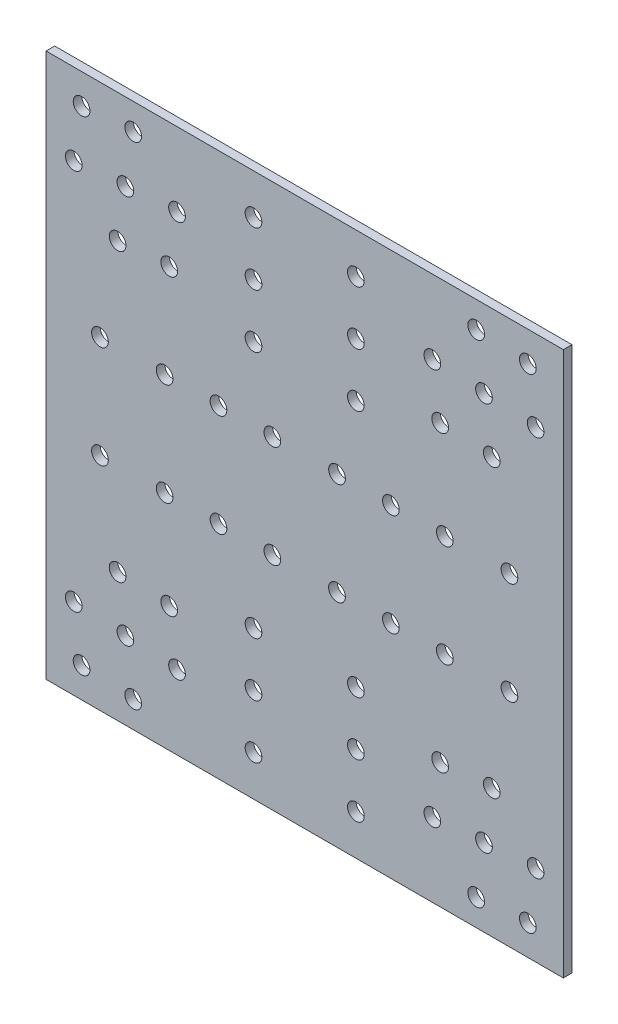
SolidWorks part; units mm, degrees
ref_plane "前视基准面" through (0, 0, 0) normal (0, 0, 1) x (1, 0, 0)
ref_plane "上视基准面" through (0, 0, 0) normal (0, 1, 0) x (1, 0, 0)
ref_plane "右视基准面" through (0, 0, 0) normal (1, 0, 0) x (0, 0, -1)
sketch "草图1" plane through (0, 0, 0) normal (0, 0, 1) x (1, 0, 0)
  line L0 (441.9641, -2319.3154) -> (441.9641, 47680.6846) construction
  line L1 (-38.0359, 30.4879) -> (921.9641, 30.4879)
  line L2 (-38.0359, 30.4879) -> (-38.0359, -979.5121)
  line L3 (-38.0359, -979.5121) -> (921.9641, -979.5121)
  line L4 (921.9641, 30.4879) -> (921.9641, -979.5121)
  line L5 (-192.1047, -474.5121) -> (1362.782, -474.5121) construction
  line L6 (27.879, -923.7944) -> (33913.7262, 35842.3499) construction
  line L7 (109.2051, -835.5556) -> (-167.3802, -580.6383) construction
  line L8 (-167.3802, -580.6383) -> (296.3288, -1008.0199) construction
  circle A0 centre (190.5311, -747.3169) radius 15.5
  circle A1 centre (27.879, -923.7944) radius 15.5
  circle A2 centre (109.2051, -835.5556) radius 15.5
  circle A3 centre (205.0173, -842.265) radius 15.5
  circle A4 centre (94.7189, -740.6075) radius 15.5
  circle A5 centre (346.9641, -904.5121) radius 15.5
  circle A6 centre (346.9641, -704.5121) radius 15.5
  circle A7 centre (346.9641, -804.5121) radius 15.5
  circle A8 centre (381.9641, -569.5121) radius 15.5
  circle A9 centre (181.9641, -569.5121) radius 15.5
  circle A10 centre (281.9641, -569.5121) radius 15.5
  circle A11 centre (61.9641, -569.5121) radius 15.5
  circle A12 centre (13.3928, -828.8462) radius 15.5
  circle A13 centre (123.6913, -930.5038) radius 15.5
  circle A14 centre (760.2369, -930.5038) radius 15.5
  circle A15 centre (870.5353, -828.8462) radius 15.5
  circle A16 centre (821.9641, -569.5121) radius 15.5
  circle A17 centre (601.9641, -569.5121) radius 15.5
  circle A18 centre (701.9641, -569.5121) radius 15.5
  circle A19 centre (501.9641, -569.5121) radius 15.5
  circle A20 centre (536.9641, -804.5121) radius 15.5
  circle A21 centre (536.9641, -704.5121) radius 15.5
  circle A22 centre (536.9641, -904.5121) radius 15.5
  circle A23 centre (789.2093, -740.6075) radius 15.5
  circle A24 centre (678.9109, -842.265) radius 15.5
  circle A25 centre (774.7231, -835.5556) radius 15.5
  circle A26 centre (856.0491, -923.7944) radius 15.5
  circle A27 centre (693.3971, -747.3169) radius 15.5
  circle A28 centre (693.3971, -201.7073) radius 15.5
  circle A29 centre (856.0491, -25.2298) radius 15.5
  circle A30 centre (774.7231, -113.4685) radius 15.5
  circle A31 centre (678.9109, -106.7591) radius 15.5
  circle A32 centre (789.2093, -208.4167) radius 15.5
  circle A33 centre (536.9641, -44.5121) radius 15.5
  circle A34 centre (536.9641, -244.5121) radius 15.5
  circle A35 centre (536.9641, -144.5121) radius 15.5
  circle A36 centre (501.9641, -379.5121) radius 15.5
  circle A37 centre (701.9641, -379.5121) radius 15.5
  circle A38 centre (601.9641, -379.5121) radius 15.5
  circle A39 centre (821.9641, -379.5121) radius 15.5
  circle A40 centre (870.5353, -120.1779) radius 15.5
  circle A41 centre (760.2369, -18.5204) radius 15.5
  circle A42 centre (123.6913, -18.5204) radius 15.5
  circle A43 centre (13.3928, -120.1779) radius 15.5
  circle A44 centre (61.9641, -379.5121) radius 15.5
  circle A45 centre (281.9641, -379.5121) radius 15.5
  circle A46 centre (181.9641, -379.5121) radius 15.5
  circle A47 centre (381.9641, -379.5121) radius 15.5
  circle A48 centre (346.9641, -144.5121) radius 15.5
  circle A49 centre (346.9641, -244.5121) radius 15.5
  circle A50 centre (346.9641, -44.5121) radius 15.5
  circle A51 centre (94.7189, -208.4167) radius 15.5
  circle A52 centre (205.0173, -106.7591) radius 15.5
  circle A53 centre (109.2051, -113.4685) radius 15.5
  circle A54 centre (27.879, -25.2298) radius 15.5
  circle A55 centre (190.5311, -201.7073) radius 15.5
  dimension "D4" = 251.433
  dimension "D5" = 31
  dimension "D7" = 31
  dimension "D10" = 31
  dimension "D14" = 31
  dimension "D13" = 31
  dimension "D19" = 31
  dimension "D22" = 31
  dimension "D24" = 31
  dimension "D26" = 31
  dimension "D29" = 31
  dimension "D31" = 31
  dimension "D33" = 31
  dimension "D1" = 505
  dimension "D2" = 1010
  dimension "D3" = 480
  dimension "D6" = 272.8048
  dimension "D8" = 240
  dimension "D9" = 65.9149
  dimension "D11" = 120
  dimension "D12" = 143.9565
  dimension "D15" = 137.2471
  dimension "D16" = 236.9468
  dimension "D17" = 132.7548
  dimension "D18" = 238.9046
  dimension "D20" = 95
  dimension "D21" = 75
  dimension "D23" = 200
  dimension "D25" = 100
  dimension "D27" = 60
  dimension "D28" = 95
  dimension "D30" = 200
  dimension "D32" = 100
  dimension "D34" = 120
  dimension "D35" = 0
extrude "拉伸3" add sketch "草图1" along normal blind 16
